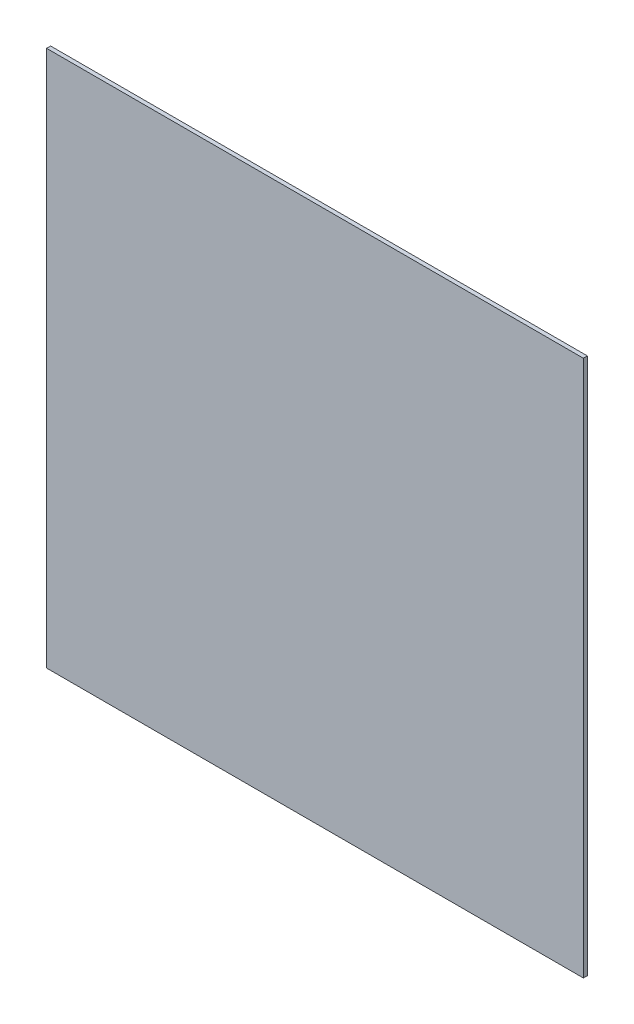
SolidWorks part; units mm, degrees
ref_plane "Front" through (0, 0, 0) normal (0, 0, 1) x (1, 0, 0)
ref_plane "Top" through (0, 0, 0) normal (0, 1, 0) x (1, 0, 0)
ref_plane "Right" through (0, 0, 0) normal (1, 0, 0) x (0, 0, -1)
other "Configuration Table"
sketch "Sketch1" plane through (0, 0, 0) normal (0, 0, 1) x (1, 0, 0)
  line L1 (0, 0) -> (40, 0)
  line L2 (0, 0) -> (0, 40)
  line L3 (0, 40) -> (40, 40)
  line L4 (40, 0) -> (40, 40)
  dimension "D1" = 40
  dimension "D2" = 40
extrude "Extrude1" add sketch "Sketch1" against normal blind 0.3
